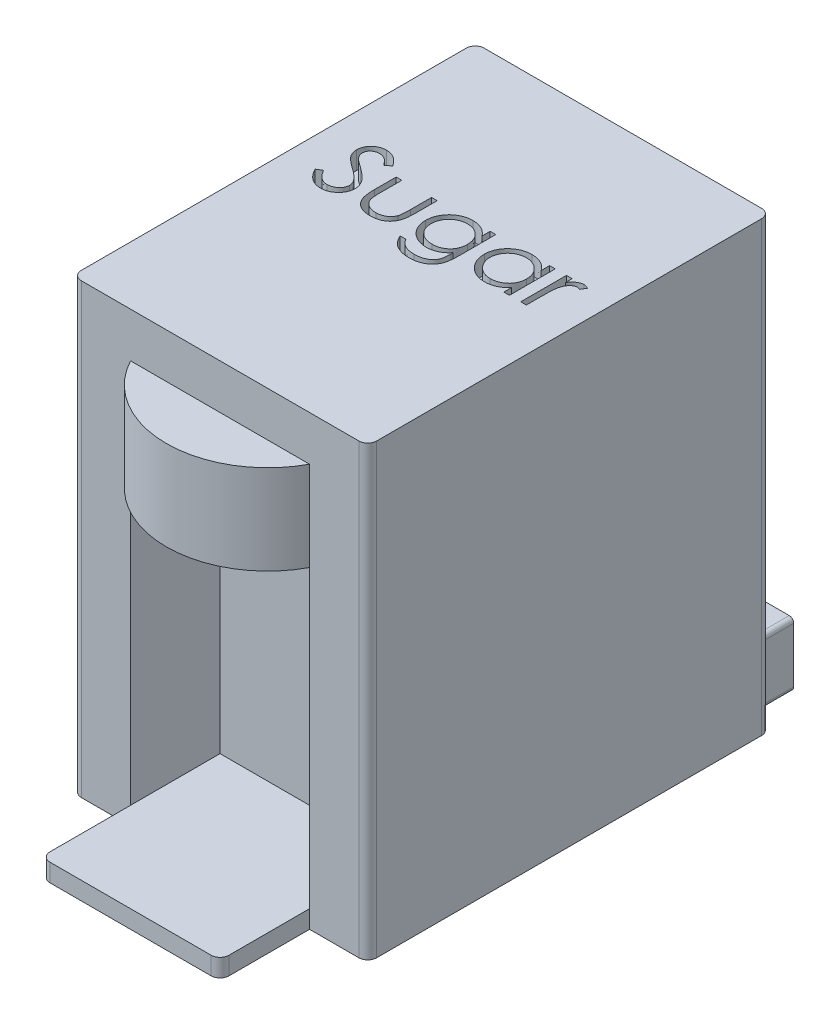
SolidWorks part; units mm, degrees
ref_plane "Front Plane" through (0, 0, 0) normal (0, 0, 1) x (1, 0, 0)
ref_plane "Top Plane" through (0, 0, 0) normal (0, 1, 0) x (1, 0, 0)
ref_plane "Right Plane" through (0, 0, 0) normal (1, 0, 0) x (0, 0, -1)
sketch "Sketch1" plane through (0, 0, 0) normal (0, 1, 0) x (1, 0, 0)
  line L1 (-165, -225) -> (165, -225)
  line L2 (-165, -225) -> (-165, 225)
  line L3 (-165, 225) -> (165, 225)
  line L4 (165, -225) -> (165, 225)
  line L5 (-165, -225) -> (165, 225) construction
  line L6 (-165, 225) -> (165, -225) construction
  point P0 (0, 0)
  dimension "D1" = 330
  dimension "D2" = 450
extrude "Boss-Extrude1" add sketch "Sketch1" along normal blind 500
sketch "Sketch2" plane through (0, 0, 225) normal (0, 0, 1) x (1, 0, 0)
  line L0 (-165, 0) -> (165, 0) construction
  line L1 (-100, 0) -> (100, 0)
  line L2 (-100, 0) -> (-100, 350)
  line L3 (-100, 350) -> (100, 350)
  line L4 (100, 0) -> (100, 350)
  point P6 (0, 0)
  dimension "D1" = 200
  dimension "D2" = 350
extrude "Cut-Extrude1" cut sketch "Sketch2" against normal blind 100
sketch "Sketch3" plane through (0, 350, 0) normal (0, -1, 0) x (1, 0, 0)
  line L0 (100, 225) -> (-100, 225) construction
  line L1 (100, 225) -> (-100, 225)
  arc A0 (-100, 225) -> (100, 225) centre (0, 171.6242) cw
extrude "Boss-Extrude2" add sketch "Sketch3" against normal blind 100
sketch "Sketch4" plane through (0, 0, 125) normal (0, 0, 1) x (1, 0, 0)
  line L0 (100, 0) -> (100, 350) construction
  line L1 (-100, 0) -> (100, 0)
  line L2 (-100, 0) -> (-100, 20)
  line L3 (-100, 20) -> (100, 20)
  line L4 (100, 0) -> (100, 20)
  dimension "D1" = 20
extrude "Boss-Extrude3" add sketch "Sketch4" along normal blind 200
sketch "Sketch5" plane through (0, 350, 0) normal (0, -1, 0) x (1, 0, 0)
  circle A0 centre (0, 203.1713) radius 58.985
extrude "Cut-Extrude2" cut sketch "Sketch5" against normal blind 50
fillet "Fillet1" radius 10 4 edges at (165, 250, 225) (-165, 250, 225) (-165, 250, -225) (165, 250, -225)
sketch "Sketch6" plane through (0, 0, -225) normal (0, 0, -1) x (-1, 0, 0)
  line L0 (-155, 0) -> (155, 0) construction
  line L1 (-140.8441, 0) -> (-32.0502, 0)
  line L2 (-140.8441, 0) -> (-140.8441, 71.4886)
  line L3 (-140.8441, 71.4886) -> (-32.0502, 71.4886)
  line L4 (-32.0502, 0) -> (-32.0502, 71.4886)
extrude "Boss-Extrude4" add sketch "Sketch6" along normal blind 50
fillet "Fillet2" radius 5 4 edges at (140.8441, 0, -250) (140.8441, 71.4886, -250) (32.0502, 0, -250) (32.0502, 71.4886, -250)
fillet "Fillet3" radius 10 2 edges at (-100, 10, 325) (100, 10, 325)
sketch "Sketch7" plane through (0, 500, 0) normal (0, 1, 0) x (1, 0, 0)
  line L0 (-165, 0) -> (165, 0) construction
  line L1 (-165, 215) -> (-165, -215) construction
  line L2 (165, -215) -> (165, 215) construction
  text T0 "Sugar" font "Century Gothic" height 70
extrude "Cut-Extrude3" cut sketch "Sketch7" against normal blind 20
